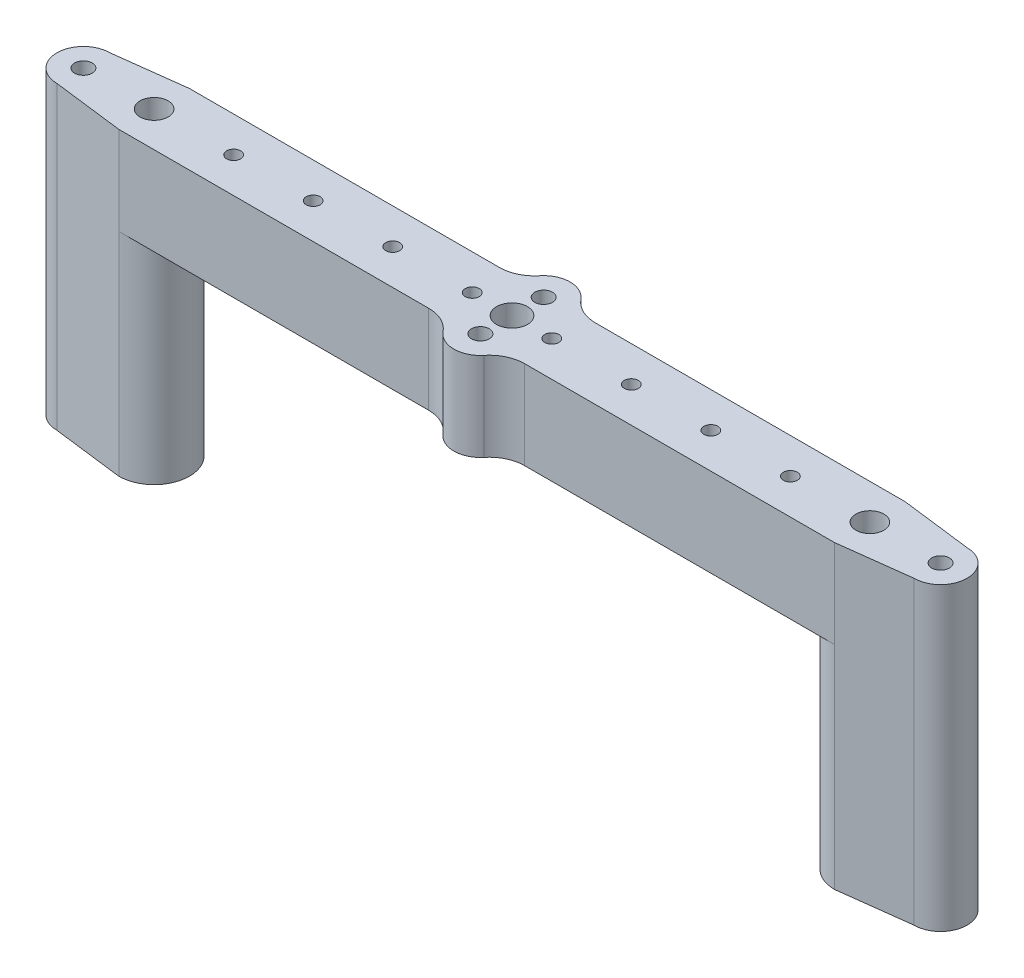
SolidWorks part; units mm, degrees
ref_plane "Front Plane" through (0, 0, 0) normal (0, 0, 1) x (1, 0, 0)
ref_plane "Top Plane" through (0, 0, 0) normal (0, 1, 0) x (1, 0, 0)
ref_plane "Right Plane" through (0, 0, 0) normal (1, 0, 0) x (0, 0, -1)
sketch "Sketch1" plane through (0, 0, 0) normal (0, 1, 0) x (1, 0, 0)
  line L2 (0, 0) -> (0, 13.1499) construction
  line L3 (-40.5, 4) -> (-48.5, 3)
  line L4 (-48.5, -3) -> (-40.5, -4)
  line L5 (48.5, -3) -> (40.5, -4)
  line L6 (40.5, 4) -> (48.5, 3)
  arc A0 (-40.5, 4) -> (-40.5, -4) centre (-40.5, 0) cw
  arc A1 (40.5, -4) -> (40.5, 4) centre (40.5, 0) cw
  arc A2 (-48.5, 3) -> (-48.5, -3) centre (-48.5, 0) ccw
  circle A3 centre (-40.5, 0) radius 1.5875
  circle A4 centre (-40.5, 0) radius 4 construction
  circle A5 centre (40.5, 0) radius 4 construction
  circle A6 centre (40.5, 0) radius 1.5875
  circle A7 centre (0, -3.5795) radius 3 construction
  circle A22 centre (48.5, 0) radius 1
  circle A23 centre (-48.5, 0) radius 1
  arc A24 (48.5, 3) -> (48.5, -3) centre (48.5, 0) cw
  circle A30 centre (0, 3.5795) radius 3 construction
  circle A34 centre (0, -3.5795) radius 1 construction
  circle A35 centre (0, 3.5795) radius 1 construction
extrude "Boss-Extrude1" add sketch "Sketch1" against normal blind 24
sketch "Sketch2" plane through (0, 0, 0) normal (0, 1, 0) x (1, 0, 0)
  line L0 (0, 0) -> (-8.0623, 0) construction
  line L2 (0, 0) -> (0, 13.1499) construction
  line L3 (-40.5, 4) -> (-48.5, 3)
  line L4 (-48.5, -3) -> (-40.5, -4)
  line L5 (48.5, -3) -> (40.5, -4)
  line L6 (40.5, 4) -> (48.5, 3)
  line L13 (-40.5, 4) -> (-5.4276, 4)
  line L14 (-40.5, -4) -> (-5.4276, -4)
  line L15 (5.4276, -4) -> (40.5, -4)
  line L16 (40.5, 4) -> (5.4276, 4)
  circle A0 centre (-31.5, 0) radius 0.7937
  circle A1 centre (-22.5, 0) radius 0.7937
  arc A2 (-48.5, 3) -> (-48.5, -3) centre (-48.5, 0) ccw
  circle A3 centre (-40.5, 0) radius 1.5875
  circle A4 centre (-40.5, 0) radius 4 construction
  circle A5 centre (40.5, 0) radius 4 construction
  circle A6 centre (40.5, 0) radius 1.5875
  circle A7 centre (0, -3.5795) radius 3 construction
  circle A8 centre (-22.5, 0) radius 2.75 construction
  circle A9 centre (-13.5, 0) radius 0.7937
  circle A10 centre (-13.5, 0) radius 2.75 construction
  circle A11 centre (-4.5, 0) radius 0.7937
  circle A12 centre (-4.5, 0) radius 2.75 construction
  circle A13 centre (4.5, 0) radius 0.7937
  circle A14 centre (-31.5, 0) radius 2.75 construction
  circle A15 centre (4.5, 0) radius 2.75 construction
  circle A16 centre (13.5, 0) radius 0.7937
  circle A17 centre (13.5, 0) radius 2.75 construction
  circle A18 centre (22.5, 0) radius 0.7937
  circle A19 centre (22.5, 0) radius 2.75 construction
  circle A20 centre (31.5, 0) radius 0.7937
  circle A21 centre (31.5, 0) radius 2.75 construction
  circle A22 centre (48.5, 0) radius 1
  circle A23 centre (-48.5, 0) radius 1
  arc A24 (48.5, 3) -> (48.5, -3) centre (48.5, 0) cw
  arc A25 (-2.3261, 5.474) -> (2.3261, 5.474) centre (0, 3.5795) cw
  arc A26 (-2.3261, 5.474) -> (-5.4276, 4) centre (-5.4276, 8) cw
  arc A27 (2.3261, 5.474) -> (5.4276, 4) centre (5.4276, 8) ccw
  arc A28 (2.3261, -5.474) -> (5.4276, -4) centre (5.4276, -8) cw
  arc A29 (-2.3261, -5.474) -> (-5.4276, -4) centre (-5.4276, -8) ccw
  circle A30 centre (0, 3.5795) radius 3 construction
  arc A31 (-2.3261, -5.474) -> (2.3261, -5.474) centre (0, -3.5795) ccw
  circle A32 centre (0, 0) radius 1.75
  circle A34 centre (0, -3.5795) radius 1
  circle A35 centre (0, 3.5795) radius 1
  dimension "D1" = 8
  dimension "D2" = 4
  dimension "D3" = 4
extrude "Boss-Extrude2" add sketch "Sketch2" along normal blind 10
ref_plane "Plane1" through (0, -24, 0) normal (0, -1, 0) x (1, 0, 0)
sketch "Sketch4" plane through (0, -24, 0) normal (0, -1, 0) x (1, 0, 0)
  line L0 (0, 0) -> (-8.0623, 0) construction
  line L2 (0, 0) -> (0, 13.1499) construction
  line L3 (-40.5, 4) -> (-48.5, 3)
  line L4 (-48.5, -3) -> (-40.5, -4)
  line L5 (48.5, -3) -> (40.5, -4)
  line L6 (40.5, 4) -> (48.5, 3)
  line L13 (-40.5, 4) -> (-5.4276, 4)
  line L14 (-40.5, -4) -> (-5.4276, -4)
  line L15 (5.4276, -4) -> (40.5, -4)
  line L16 (40.5, 4) -> (5.4276, 4)
  circle A0 centre (-31.5, 0) radius 0.7937
  circle A1 centre (-22.5, 0) radius 0.7937
  arc A2 (-48.5, 3) -> (-48.5, -3) centre (-48.5, 0) ccw
  circle A3 centre (-40.5, 0) radius 1.5875
  circle A4 centre (-40.5, 0) radius 4 construction
  circle A5 centre (40.5, 0) radius 4 construction
  circle A6 centre (40.5, 0) radius 1.5875
  circle A7 centre (0, -3.5795) radius 3 construction
  circle A8 centre (-22.5, 0) radius 2.75 construction
  circle A9 centre (-13.5, 0) radius 0.7937
  circle A10 centre (-13.5, 0) radius 2.75 construction
  circle A11 centre (-4.5, 0) radius 0.7937
  circle A12 centre (-4.5, 0) radius 2.75 construction
  circle A13 centre (4.5, 0) radius 0.7937
  circle A14 centre (-31.5, 0) radius 2.75 construction
  circle A15 centre (4.5, 0) radius 2.75 construction
  circle A16 centre (13.5, 0) radius 0.7937
  circle A17 centre (13.5, 0) radius 2.75 construction
  circle A18 centre (22.5, 0) radius 0.7937
  circle A19 centre (22.5, 0) radius 2.75 construction
  circle A20 centre (31.5, 0) radius 0.7937
  circle A21 centre (31.5, 0) radius 2.75 construction
  circle A22 centre (48.5, 0) radius 1
  circle A23 centre (-48.5, 0) radius 1
  arc A24 (48.5, 3) -> (48.5, -3) centre (48.5, 0) cw
  arc A25 (-2.3261, 5.474) -> (2.3261, 5.474) centre (0, 3.5795) cw
  arc A26 (-2.3261, 5.474) -> (-5.4276, 4) centre (-5.4276, 8) cw
  arc A27 (2.3261, 5.474) -> (5.4276, 4) centre (5.4276, 8) ccw
  arc A28 (2.3261, -5.474) -> (5.4276, -4) centre (5.4276, -8) cw
  arc A29 (-2.3261, -5.474) -> (-5.4276, -4) centre (-5.4276, -8) ccw
  circle A30 centre (0, 3.5795) radius 3 construction
  arc A31 (-2.3261, -5.474) -> (2.3261, -5.474) centre (0, -3.5795) ccw
  circle A32 centre (0, 0) radius 1.75
  circle A34 centre (0, -3.5795) radius 1
  circle A35 centre (0, 3.5795) radius 1
  dimension "D1" = 8
  dimension "D2" = 4
  dimension "D3" = 4
hole_wizard "M3x0.5 Tapped Hole1" positions "3DSketch2" profile "Sketch5" tap size "M3x0.5" standard "Ansi Metric"
sketch3d "3DSketch2"
  point P0 (-48.5, -24, 0)
  point P4 (48.5, -24, 0)
sketch "Sketch5" plane through (-48.5, -24, 0) normal (1, 0, 0) x (0, 0, -1)
  line L0 (0, 0) -> (0, 19.2511)
  line L1 (0, 19.2511) -> (1.25, 18.5)
  line L2 (1.25, 18.5) -> (1.25, 0)
  line L5 (1.25, 0) -> (0, 0)
  line L10 (0, 19.2511) -> (-1.25, 18.5) construction
  line L11 (0, -6.35) -> (0, 107.95) construction
  dimension "Tap Drill Dia." = 2.5
  dimension "Tap Drill Depth" = 18.5
  dimension "Drill Angle" = 118
cosmetic thread "Hole Thread1" parameters "D1"=6, "D2"=3
cosmetic thread "Hole Thread2" parameters "D1"=6, "D2"=3
